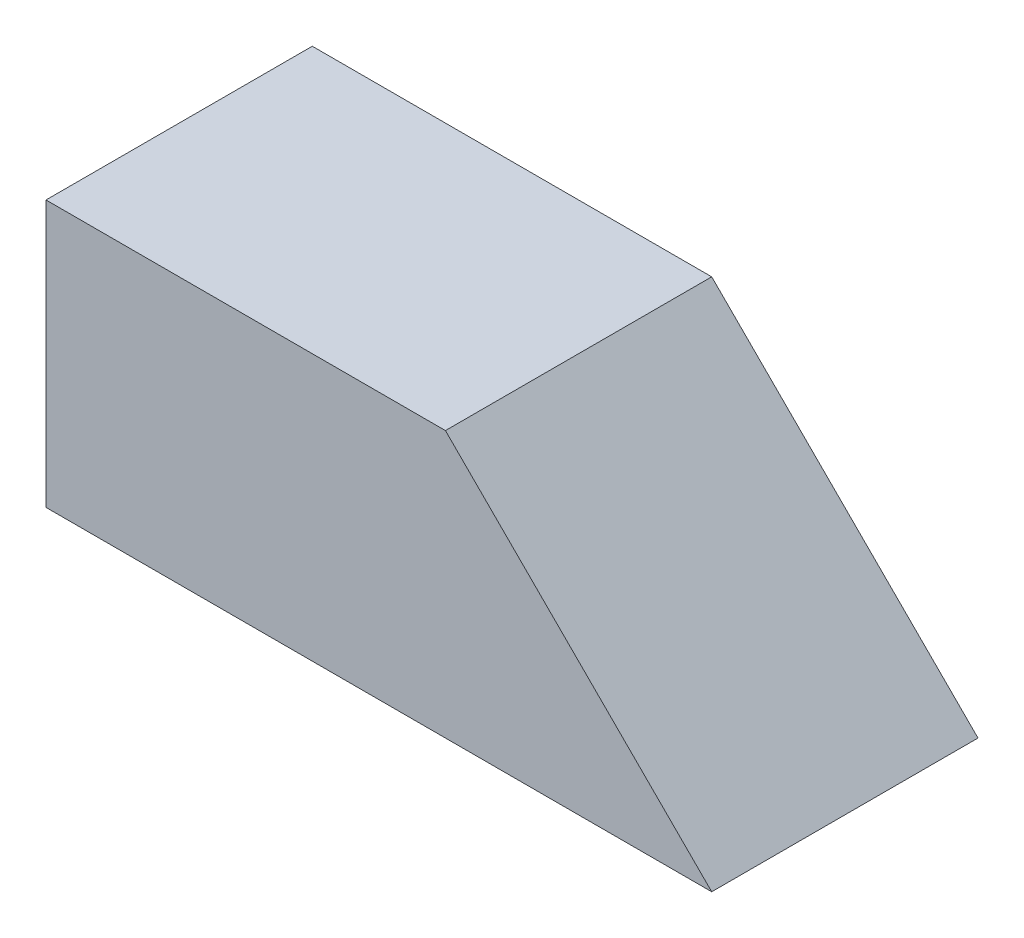
SolidWorks part; units mm, degrees
ref_plane "Front Plane" through (0, 0, 0) normal (0, 0, 1) x (1, 0, 0)
ref_plane "Top Plane" through (0, 0, 0) normal (0, 1, 0) x (1, 0, 0)
ref_plane "Right Plane" through (0, 0, 0) normal (1, 0, 0) x (0, 0, -1)
sketch "Sketch2" plane through (0, 0, 0) normal (0, 0, 1) x (1, 0, 0)
  line L0 (-113.733, 21.444) -> (-113.733, 1.444)
  line L1 (-113.733, 1.444) -> (-63.733, 1.444)
  line L2 (-63.733, 1.444) -> (-83.733, 21.444)
  line L3 (-83.733, 21.444) -> (-113.733, 21.444)
  dimension "D1" = 50
  dimension "D2" = 20
  dimension "D3" = 45
extrude "Boss-Extrude3" add sketch "Sketch2" along normal blind 20 contours L1 L2 L3 L0
